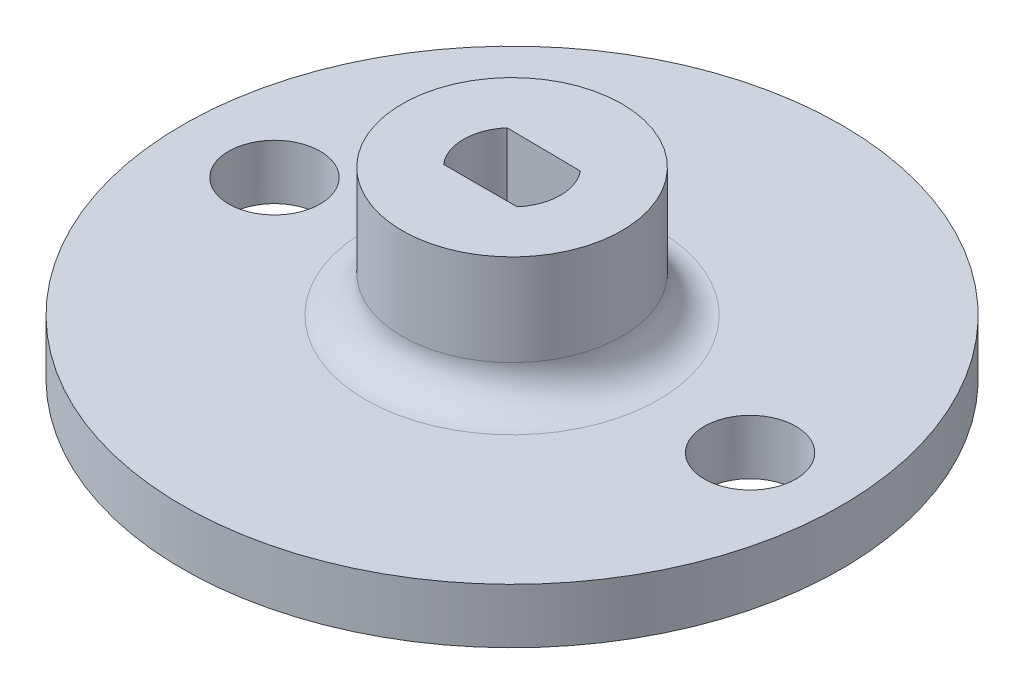
SolidWorks part; units mm, degrees
ref_plane "Front Plane" through (0, 0, 0) normal (0, 0, 1) x (1, 0, 0)
ref_plane "Top Plane" through (0, 0, 0) normal (0, 1, 0) x (1, 0, 0)
ref_plane "Right Plane" through (0, 0, 0) normal (1, 0, 0) x (0, 0, -1)
sketch "Sketch1" plane through (0, 0, 0) normal (0, 1, 0) x (1, 0, 0)
  circle A0 centre (0, 0) radius 18
  circle A1 centre (0, 0) radius 6
  circle A6 centre (0, 11) radius 2.5
  circle A7 centre (0, -11) radius 2.5
  circle A8 centre (0, 0) radius 2.6
  dimension "D1" = 12
  dimension "D2" = 36
  dimension "D3" = 5
  dimension "D4" = 5
  dimension "D5" = 11
  dimension "D7" = 5.2
  dimension "D6" = 11
extrude "Boss-Extrude6" add sketch "Sketch1" along normal blind 7 contours A1
sketch "Sketch5" plane through (0, 0, 0) normal (0, -1, 0) x (-1, 0, 0)
  circle A0 centre (0, 0) radius 18
extrude "Boss-Extrude7" add sketch "Sketch5" along normal blind 3
sketch "Sketch6" plane through (0, 7, 0) normal (0, 1, 0) x (1, 0, 0)
  line L0 (-1.9326, 1.5) -> (1.9326, 1.5)
  line L1 (-1.9326, -1.5) -> (1.9326, -1.5)
  line L2 (-44.2539, 0) -> (44.2539, 0) construction
  arc A0 (-1.9326, 1.5) -> (-1.9326, -1.5) centre (0, 0) ccw
  arc A1 (-1.9326, 1.5) -> (-1.9326, -1.5) centre (0, 0) ccw
  arc A2 (-1.9326, -1.5) -> (-1.9353, 1.4965) centre (0, 0) cw
  arc A3 (1.931, -1.502) -> (1.9326, 1.5) centre (0, 0) ccw
  circle A4 centre (11, 0) radius 2.5
  circle A5 centre (-11, 0) radius 2.5
  dimension "D1" = 1.5
  dimension "D3" = 11
  dimension "D2" = 1.5
  dimension "D4" = 11
extrude "Cut-Extrude2" cut sketch "Sketch6" against normal blind 6 contours L1 A3 L0 A0 A1
fillet "Fillet1" radius 2 1 edges at (0, 0, 6)
sketch "Sketch8" plane through (0, 0, 0) normal (0, 1, 0) x (1, 0, 0)
  line L0 (-44.2539, 0) -> (44.2539, 0) construction
  circle A0 centre (13, 0) radius 2.5
  circle A1 centre (-13, 0.0221) radius 2.5
  dimension "D1" = 13
  dimension "D2" = 13
extrude "Cut-Extrude3" cut sketch "Sketch8" against normal blind 6
sketch "Sketch9" plane through (0, 7, 0) normal (0, 1, 0) x (1, 0, 0)
  line L0 (-2.0042, 1.7337) -> (2.0438, 1.6868)
  line L1 (-2.0042, -1.7337) -> (2.0042, -1.7337)
  arc A0 (-2.0042, 1.7337) -> (-2.0042, -1.7337) centre (0, 0) ccw
  arc A1 (2.0042, -1.7337) -> (2.0438, 1.6868) centre (0, 0) ccw
  dimension "D1" = 5.3
extrude "Cut-Extrude4" cut sketch "Sketch9" against normal blind 8
